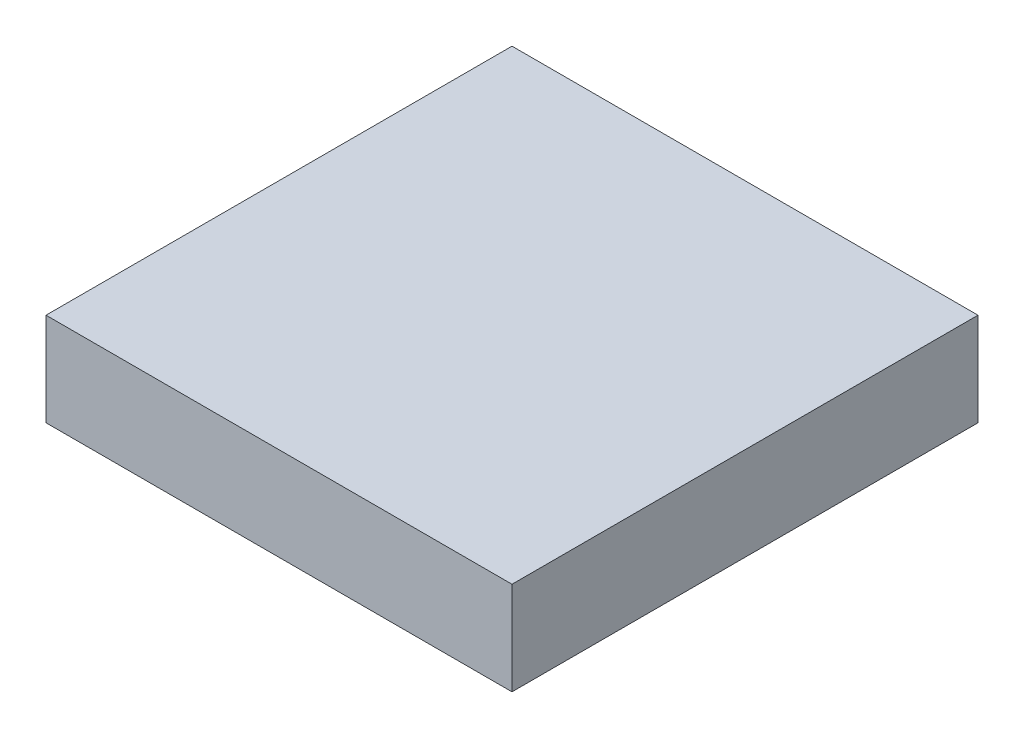
SolidWorks part; units mm, degrees
ref_plane "Front Plane" through (0, 0, 0) normal (0, 0, 1) x (1, 0, 0)
ref_plane "Top Plane" through (0, 0, 0) normal (0, 1, 0) x (1, 0, 0)
ref_plane "Right Plane" through (0, 0, 0) normal (1, 0, 0) x (0, 0, -1)
sketch "Sketch1" plane through (0, 0, 0) normal (0, 1, 0) x (1, 0, 0)
  line L1 (0, 0) -> (35, 0)
  line L2 (0, 0) -> (0, 35)
  line L3 (0, 35) -> (35, 35)
  line L4 (35, 0) -> (35, 35)
  dimension "D1" = 35
extrude "Boss-Extrude1" add sketch "Sketch1" along normal blind 7
